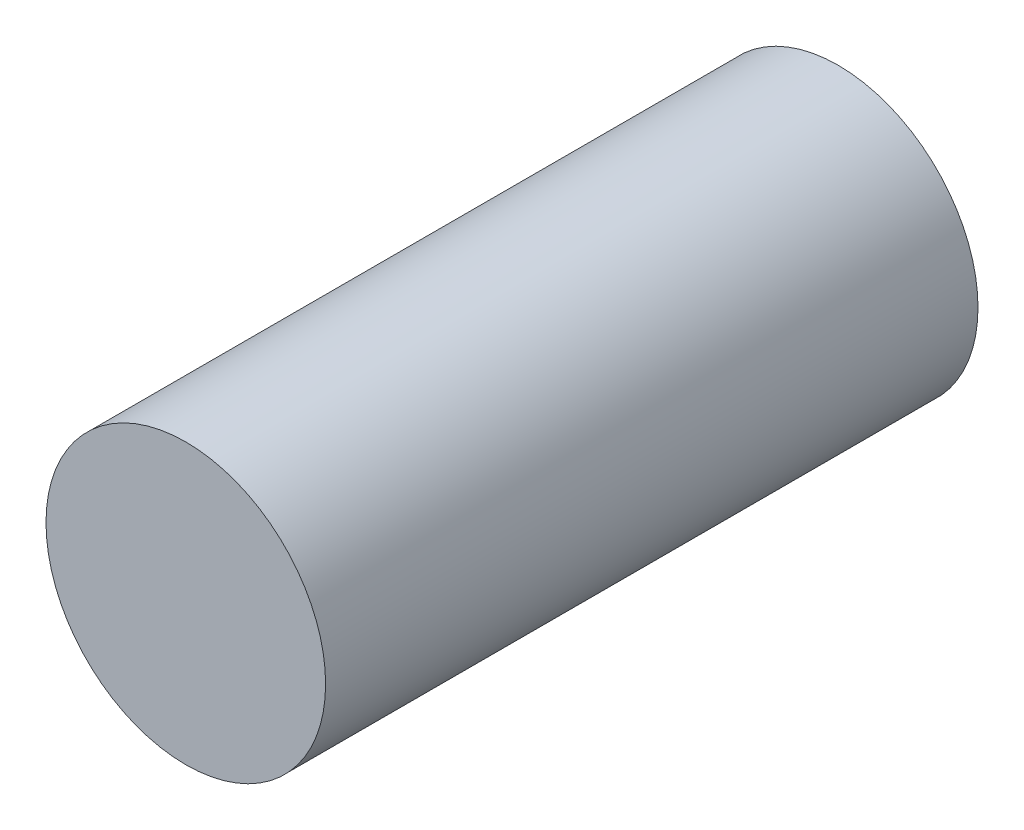
SolidWorks part; units mm, degrees
material "1.3505 (100Cr6) hardened 60 HRC"
ref_plane "Front Plane" through (0, 0, 0) normal (0, 0, 1) x (1, 0, 0)
ref_plane "Top Plane" through (0, 0, 0) normal (0, 1, 0) x (1, 0, 0)
ref_plane "Right Plane" through (0, 0, 0) normal (1, 0, 0) x (0, 0, -1)
sketch "Sketch1" plane through (0, 0, 0) normal (0, 0, 1) x (1, 0, 0)
  circle A0 centre (0, 0) radius 6
  dimension "D1" = 12
extrude "EX_Planet_Pin_Ø12x24" add sketch "Sketch1" along normal mid plane 28
